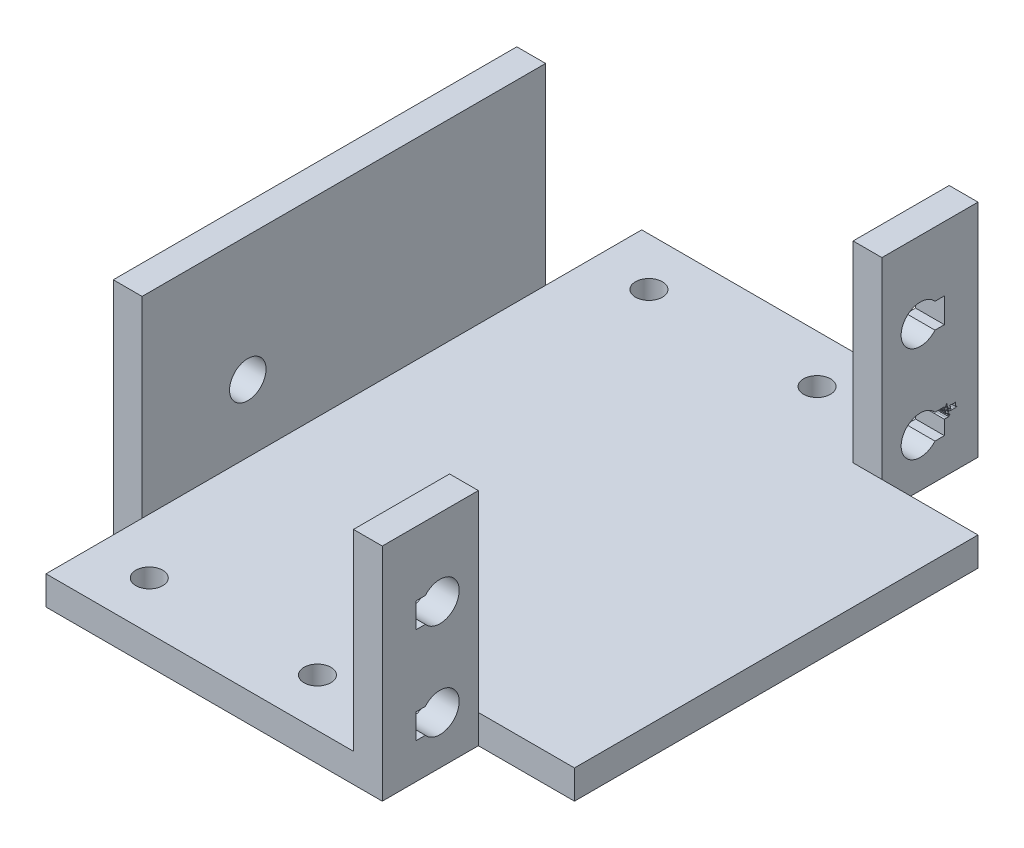
SolidWorks part; units mm, degrees
ref_plane "前视基准面" through (0, 0, 0) normal (0, 0, 1) x (1, 0, 0)
ref_plane "上视基准面" through (0, 0, 0) normal (0, 1, 0) x (1, 0, 0)
ref_plane "右视基准面" through (0, 0, 0) normal (1, 0, 0) x (0, 0, -1)
sketch "草图1" plane through (0, 0, 0) normal (0, 1, 0) x (1, 0, 0)
  line L0 (-21, -21) -> (-21, -31)
  line L1 (-21, 21) -> (-21, -21)
  line L2 (-21, 31) -> (-21, 21)
  line L3 (11, 31) -> (-21, 31)
  line L4 (11, 21) -> (11, 31)
  line L5 (14, 21) -> (11, 21)
  line L6 (24, 21) -> (14, 21)
  line L7 (24, -21) -> (24, 21)
  line L8 (14, -21) -> (24, -21)
  line L9 (11, -21) -> (14, -21)
  line L10 (11, -31) -> (11, -21)
  line L11 (-21, -31) -> (11, -31)
  line L12 (-24, 21) -> (-21, 21)
  line L13 (-21, 21) -> (-21, -21)
  line L14 (-21, -21) -> (-24, -21)
  line L15 (-24, -21) -> (-24, 21)
  line L16 (11, 21) -> (11, 31)
  line L17 (11, 31) -> (14, 31)
  line L18 (14, 31) -> (14, 21)
  line L19 (14, 21) -> (11, 21)
  line L20 (11, -31) -> (11, -21)
  line L21 (11, -21) -> (14, -21)
  line L22 (14, -21) -> (14, -31)
  line L23 (14, -31) -> (11, -31)
  circle A0 centre (-15.25, 26) radius 1.4
  circle A1 centre (2.25, 26) radius 1.4
  circle A2 centre (-15.25, -26) radius 1.4
  circle A3 centre (2.25, -26) radius 1.4
  dimension "D1" = 48
sketch "草图2" plane through (0, 0, 0) normal (0, 1, 0) x (1, 0, 0)
  line L0 (14, 21) -> (11, 21) construction
  line L1 (24, 21) -> (14, 21) construction
  line L2 (24, -21) -> (24, 21) construction
  line L3 (14, -21) -> (24, -21) construction
  line L4 (11, -21) -> (14, -21) construction
  line L5 (11, -31) -> (11, -21) construction
  line L6 (-21, -31) -> (11, -31) construction
  line L7 (-21, -21) -> (-21, -31) construction
  line L8 (-21, 21) -> (-21, -21) construction
  line L9 (-21, 31) -> (-21, 21) construction
  line L10 (11, 31) -> (-21, 31) construction
  line L11 (11, 21) -> (11, 31) construction
  line L12 (14, 21) -> (11, 21)
  line L13 (24, 21) -> (14, 21)
  line L14 (24, -21) -> (24, 21)
  line L15 (14, -21) -> (24, -21)
  line L16 (11, -21) -> (14, -21)
  line L17 (11, -31) -> (11, -21)
  line L18 (-21, -31) -> (11, -31)
  line L19 (-21, -21) -> (-21, -31)
  line L20 (-21, 21) -> (-21, -21)
  line L21 (-21, 31) -> (-21, 21)
  line L22 (11, 31) -> (-21, 31)
  line L23 (11, 21) -> (11, 31)
  circle A0 centre (-15.25, -26) radius 1.4 construction
  circle A1 centre (2.25, -26) radius 1.4 construction
  circle A2 centre (-15.25, 26) radius 1.4 construction
  circle A3 centre (2.25, 26) radius 1.4 construction
  circle A4 centre (-15.25, -26) radius 1.4
  circle A5 centre (2.25, -26) radius 1.4
  circle A6 centre (-15.25, 26) radius 1.4
  circle A7 centre (2.25, 26) radius 1.4
extrude "凸台-拉伸1" add sketch "草图2" along normal blind 3
sketch "草图3" plane through (0, 0, 0) normal (0, 1, 0) x (1, 0, 0)
  line L0 (14, 21) -> (11, 21) construction
  line L1 (11, 21) -> (11, 31) construction
  line L2 (14, 31) -> (14, 21) construction
  line L3 (11, 31) -> (14, 31) construction
  line L4 (14, -31) -> (11, -31) construction
  line L5 (11, -31) -> (11, -21) construction
  line L6 (11, -21) -> (14, -21) construction
  line L7 (14, -21) -> (14, -31) construction
  line L8 (-21, -21) -> (-24, -21) construction
  line L9 (-24, -21) -> (-24, 21) construction
  line L10 (-21, 21) -> (-21, -21) construction
  line L11 (-24, 21) -> (-21, 21) construction
  line L12 (14, 21) -> (11, 21)
  line L13 (11, 21) -> (11, 31)
  line L14 (14, 31) -> (14, 21)
  line L15 (11, 31) -> (14, 31)
  line L16 (14, -31) -> (11, -31)
  line L17 (11, -31) -> (11, -21)
  line L18 (11, -21) -> (14, -21)
  line L19 (14, -21) -> (14, -31)
  line L20 (-21, -21) -> (-24, -21)
  line L21 (-24, -21) -> (-24, 21)
  line L22 (-21, 21) -> (-21, -21)
  line L23 (-24, 21) -> (-21, 21)
extrude "凸台-拉伸2" add sketch "草图3" along normal blind 23
sketch "草图4" plane through (-24, 0, 0) normal (-1, 0, 0) x (0, 0, 1)
  circle A0 centre (10.0002, 10) radius 1.9
  point P6 (-20.9997, 23)
  point P9 (-21, 23)
  point P12 (21, 0)
extrude "切除-拉伸1" cut sketch "草图4" against normal blind 3
sketch "草图5" plane through (14, 0, 0) normal (1, 0, 0) x (0, 0, -1)
  line L0 (27.5001, 16.3001) -> (26.5199, 16.3001)
  line L1 (27.5001, 13.7001) -> (27.5001, 16.3001)
  line L2 (26.5199, 13.7001) -> (27.5001, 13.7001)
  line L3 (-26.5198, 6.3001) -> (-27.4999, 6.3001)
  line L4 (-27.4999, 6.3001) -> (-27.4999, 3.7001)
  line L5 (-27.4999, 3.7001) -> (-26.5198, 3.7001)
  line L6 (-27.4999, 16.3001) -> (-27.4999, 13.7001)
  line L7 (-26.5198, 16.3001) -> (-27.4999, 16.3001)
  line L8 (-27.4999, 13.7001) -> (-26.5198, 13.7001)
  line L19 (27.5001, 6.1159) -> (27.553, 6.1414)
  line L20 (27.5001, 6.095) -> (27.5001, 6.1159)
  line L21 (27.5012, 6.096) -> (27.5001, 6.095)
  line L22 (27.5485, 5.9969) -> (27.5335, 6.096)
  line L23 (27.5635, 5.9234) -> (27.5485, 5.9969)
  line L24 (27.8119, 5.9192) -> (27.5635, 5.9234)
  line L25 (27.8032, 5.971) -> (27.8119, 5.9192)
  line L26 (27.8096, 6.2363) -> (27.7383, 6.1673)
  line L27 (27.8505, 6.1305) -> (27.8397, 6.2277)
  line L28 (27.8636, 6.0333) -> (27.8505, 6.1305)
  line L29 (27.8873, 5.917) -> (27.8636, 6.0333)
  line L30 (28.159, 5.9106) -> (27.8873, 5.917)
  line L31 (28.1289, 6.0637) -> (28.159, 5.9106)
  line L32 (28.0621, 6.0937) -> (28.1289, 6.0637)
  line L33 (28.1203, 6.1736) -> (28.0554, 6.1219)
  line L34 (28.5409, 6.1091) -> (28.3124, 6.1305)
  line L35 (28.5949, 6.1455) -> (28.5409, 6.1091)
  line L36 (28.6467, 6.0615) -> (28.6381, 6.1478)
  line L37 (28.6576, 5.9624) -> (28.6467, 6.0615)
  line L38 (28.6921, 5.7185) -> (28.6576, 5.9624)
  line L39 (28.8129, 5.714) -> (28.6921, 5.7185)
  line L40 (28.8215, 5.6795) -> (28.8474, 5.6881)
  line L41 (28.7803, 5.6645) -> (28.8215, 5.6795)
  line L42 (28.7285, 5.6472) -> (28.7803, 5.6645)
  line L43 (28.5323, 5.6536) -> (28.5818, 5.6536)
  line L44 (28.2002, 5.645) -> (28.5323, 5.6536)
  line L45 (28.0513, 5.6364) -> (28.2002, 5.645)
  line L46 (28.0426, 5.6622) -> (28.0513, 5.6364)
  line L47 (28.2002, 5.7012) -> (28.0426, 5.6622)
  line L48 (28.1698, 5.848) -> (28.2002, 5.7012)
  line L49 (27.8937, 5.8566) -> (28.1698, 5.848)
  line L50 (27.9154, 5.7594) -> (27.8937, 5.8566)
  line L51 (27.9304, 5.7035) -> (27.9154, 5.7594)
  line L52 (27.9413, 5.6603) -> (27.9304, 5.7035)
  line L53 (27.9541, 5.6172) -> (27.9413, 5.6603)
  line L54 (27.8914, 5.5632) -> (27.924, 5.5913)
  line L55 (27.8569, 5.645) -> (27.8656, 5.5696)
  line L56 (27.8441, 5.7422) -> (27.8569, 5.645)
  line L57 (27.8246, 5.8566) -> (27.8441, 5.7422)
  line L58 (27.5788, 5.863) -> (27.8246, 5.8566)
  line L59 (27.5894, 5.8176) -> (27.5788, 5.863)
  line L60 (27.6047, 5.768) -> (27.5894, 5.8176)
  line L61 (27.6198, 5.7227) -> (27.6047, 5.768)
  line L62 (27.6025, 5.7054) -> (27.6198, 5.7227)
  line L63 (27.5744, 5.6754) -> (27.6025, 5.7054)
  line L64 (28.0771, 5.3452) -> (28.0468, 5.3755)
  line L65 (28.0449, 5.3302) -> (28.0771, 5.3452)
  line L66 (28.0209, 5.3452) -> (28.0449, 5.3302)
  line L67 (27.9822, 5.3733) -> (28.0209, 5.3452)
  line L68 (27.8895, 5.4401) -> (27.9822, 5.3733)
  line L69 (27.8397, 5.4705) -> (27.8895, 5.4401)
  line L70 (27.8828, 5.2503) -> (27.8397, 5.4705)
  line L71 (28.0103, 5.2503) -> (27.8828, 5.2503)
  line L72 (27.9845, 5.1943) -> (28.0295, 5.2093)
  line L73 (27.9391, 5.179) -> (27.9845, 5.1943)
  line L74 (27.7211, 5.1876) -> (27.7534, 5.1898)
  line L75 (27.5001, 5.1815) -> (27.7211, 5.1876)
  line L76 (27.5001, 3.7001) -> (27.5001, 5.1815)
  line L77 (26.5199, 3.7001) -> (27.5001, 3.7001)
  line L78 (27.5001, 6.3001) -> (26.5199, 6.3001)
  line L79 (27.5001, 6.1926) -> (27.5001, 6.3001)
  line L80 (27.747, 6.4693) -> (27.7061, 6.4693)
  line L81 (27.7837, 6.2472) -> (27.747, 6.4693)
  line L82 (27.6629, 6.1909) -> (27.7837, 6.2472)
  line L83 (27.553, 6.1414) -> (27.6629, 6.1909)
  arc A0 (26.5199, 6.3001) -> (26.5199, 3.7001) centre (25.0001, 5.0001) ccw
  arc A1 (26.5199, 16.3001) -> (26.5199, 13.7001) centre (25.0001, 15.0001) ccw
  arc A2 (-26.5198, 3.7001) -> (-26.5198, 6.3001) centre (-24.9999, 5.0001) ccw
  arc A3 (-26.5198, 13.7001) -> (-26.5198, 16.3001) centre (-24.9999, 15.0001) ccw
  spline S0 degree 3 poles (27.5335, 6.096) (27.5329, 6.0985) (27.5319, 6.1038) (27.5225, 6.1064) (27.5116, 6.1044) (27.505, 6.0991) (27.5012, 6.096) knots 0 0 0 0 0.179713 0.377228 0.636241 1 1 1 1
  spline S1 degree 3 poles (27.7383, 6.1673) (27.7461, 6.1537) (27.7621, 6.1256) (27.7792, 6.0784) (27.7941, 6.0267) (27.8001, 5.9901) (27.8032, 5.971) knots 0 0 0 0 0.224767 0.465017 0.721859 1 1 1 1
  spline S2 degree 3 poles (27.8397, 6.2277) (27.8395, 6.2319) (27.8393, 6.2396) (27.8286, 6.2447) (27.8181, 6.243) (27.8126, 6.2386) (27.8096, 6.2363) knots 0 0 0 0 0.278674 0.501817 0.738014 1 1 1 1
  spline S3 degree 3 poles (28.0554, 6.1219) (28.0529, 6.1194) (28.0485, 6.1151) (28.0462, 6.1057) (28.0525, 6.0979) (28.0585, 6.0953) (28.0621, 6.0937) knots 0 0 0 0 0.281514 0.478154 0.690744 1 1 1 1
  spline S4 degree 3 poles (28.3124, 6.1305) (28.3036, 6.1311) (28.2874, 6.1323) (28.265, 6.1356) (28.2462, 6.1376) (28.227, 6.1419) (28.2072, 6.1484) (28.1888, 6.1606) (28.1756, 6.1727) (28.1646, 6.1809) (28.1557, 6.1859) (28.1484, 6.1882) (28.1421, 6.1871) (28.1359, 6.1846) (28.1287, 6.1797) (28.1233, 6.1758) (28.1203, 6.1736) knots 0 0 0 0 0.125291 0.232736 0.323379 0.395045 0.513019 0.619858 0.707379 0.7695 0.814456 0.853596 0.875126 0.904529 0.947615 1 1 1 1
  spline S5 degree 3 poles (28.6381, 6.1478) (28.638, 6.1515) (28.6378, 6.1578) (28.6301, 6.1626) (28.6231, 6.1611) (28.6156, 6.158) (28.606, 6.1525) (28.5989, 6.148) (28.5949, 6.1455) knots 0 0 0 0 0.185257 0.317166 0.413974 0.553656 0.75361 1 1 1 1
  spline S6 degree 3 poles (28.8474, 5.6881) (28.8505, 5.69) (28.8555, 5.6931) (28.8614, 5.6976) (28.8636, 5.7031) (28.8601, 5.7078) (28.8531, 5.7099) (28.8431, 5.7123) (28.8292, 5.7132) (28.8188, 5.7137) (28.8129, 5.714) knots 0 0 0 0 0.141768 0.235175 0.297187 0.352718 0.446125 0.581479 0.765406 1 1 1 1
  spline S7 degree 3 poles (28.5818, 5.6536) (28.5931, 5.6528) (28.6148, 5.6513) (28.6409, 5.6455) (28.6596, 5.6407) (28.6711, 5.638) (28.6802, 5.6365) (28.6876, 5.6351) (28.6952, 5.6356) (28.7042, 5.6382) (28.7157, 5.6419) (28.724, 5.6454) (28.7285, 5.6472) knots 0 0 0 0 0.224188 0.4347 0.5311 0.609485 0.669941 0.71503 0.759716 0.821062 0.90172 1 1 1 1
  spline S8 degree 3 poles (27.924, 5.5913) (27.9284, 5.5948) (27.9359, 5.6009) (27.9455, 5.6084) (27.9514, 5.6134) (27.9535, 5.6163) (27.9541, 5.6172) knots 0 0 0 0 0.423095 0.73194 0.919611 1 1 1 1
  spline S9 degree 3 poles (27.8656, 5.5696) (27.866, 5.5655) (27.8668, 5.5591) (27.8757, 5.5541) (27.8838, 5.5582) (27.8888, 5.5614) (27.8914, 5.5632) knots 0 0 0 0 0.313511 0.50188 0.732166 1 1 1 1
  spline S10 degree 3 poles (28.0468, 5.3755) (28.0374, 5.3844) (28.0167, 5.4037) (27.9813, 5.4333) (27.9383, 5.4655) (27.898, 5.4946) (27.8614, 5.5194) (27.8298, 5.5393) (27.7951, 5.5599) (27.7572, 5.5815) (27.716, 5.6037) (27.6717, 5.627) (27.6242, 5.6511) (27.5913, 5.6671) (27.5744, 5.6754) knots 0 0 0 0 0.068855 0.151247 0.246266 0.355532 0.416602 0.482583 0.55479 0.631996 0.715503 0.804832 0.899235 1 1 1 1
  spline S11 degree 3 poles (28.0295, 5.2093) (28.035, 5.2112) (28.0449, 5.2146) (28.0579, 5.2197) (28.0681, 5.224) (28.0749, 5.2282) (28.0791, 5.2316) (28.0799, 5.2361) (28.0756, 5.2388) (28.063, 5.2427) (28.0405, 5.2472) (28.0203, 5.2493) (28.0103, 5.2503) knots 0 0 0 0 0.13348 0.242103 0.326053 0.38701 0.427187 0.449536 0.479255 0.529229 0.76642 1 1 1 1
  spline S12 degree 3 poles (27.7534, 5.1898) (27.759, 5.1897) (27.7727, 5.1894) (27.7946, 5.1864) (27.817, 5.1844) (27.837, 5.1822) (27.8556, 5.1803) (27.8736, 5.1749) (27.8893, 5.1707) (27.9005, 5.1679) (27.9081, 5.1692) (27.9158, 5.1711) (27.9264, 5.1749) (27.9345, 5.1775) (27.9391, 5.179) knots 0 0 0 0 0.089603 0.217028 0.349494 0.446323 0.53664 0.644816 0.742758 0.797476 0.823041 0.864835 0.923602 1 1 1 1
  spline S13 degree 3 poles (27.7061, 6.4693) (27.7044, 6.4579) (27.7012, 6.4359) (27.6941, 6.4043) (27.6855, 6.3758) (27.6761, 6.3497) (27.6646, 6.3269) (27.652, 6.3067) (27.638, 6.2892) (27.6158, 6.2694) (27.5829, 6.2459) (27.5424, 6.2184) (27.5136, 6.2007) (27.5001, 6.1926) knots 0.618133 0.618133 0.618133 0.618133 0.654492 0.688199 0.719732 0.748405 0.77542 0.800001 0.823378 0.845704 0.893426 0.950483 1 1 1 1
extrude "切除-拉伸2" cut sketch "草图5" against normal up to surface (3 mm away) up to face at (11, 13, -26)
